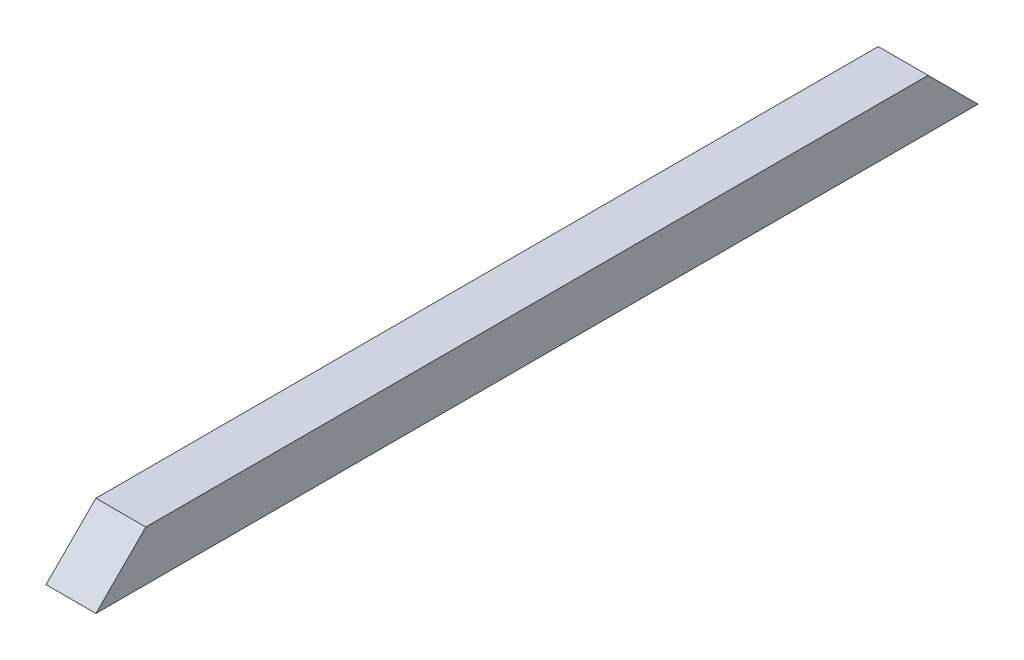
SolidWorks part; units mm, degrees
material "Plain Carbon Steel"
ref_plane "Front Plane" through (0, 0, 0) normal (0, 0, 1) x (1, 0, 0)
ref_plane "Top Plane" through (0, 0, 0) normal (0, 1, 0) x (1, 0, 0)
ref_plane "Right Plane" through (0, 0, 0) normal (1, 0, 0) x (0, 0, -1)
sketch "Sketch1" plane through (0, 0, 0) normal (0, 0, 1) x (1, 0, 0)
  line L1 (0, 0) -> (20, 0)
  line L2 (0, 0) -> (0, -20)
  line L3 (0, -20) -> (20, -20)
  line L4 (20, 0) -> (20, -20)
  dimension "D1" = 20
extrude "Boss-Extrude1" add sketch "Sketch1" along normal blind 600
sketch "Sketch2" plane through (20, 0, 0) normal (1, 0, 0) x (0, 0, -1)
  line L0 (-600, -20) -> (-600, 0)
  line L1 (-600, 0) -> (-580, 0)
  line L2 (-600, 0) -> (0, 0) construction
  line L3 (-580, 0) -> (-600, -20)
  line L4 (-266.4373, 0) -> (-246.4466, -20)
  line L5 (-578.7868, 312.3402) -> (517.2287, -783.6753) construction
  line L6 (-600, -20) -> (0, -20) construction
  line L7 (-246.4466, -20) -> (0, -20)
  line L8 (0, -20) -> (0, 0)
  line L9 (0, 0) -> (-266.4373, 0)
extrude "Cut-Extrude1" cut sketch "Sketch2" against normal through all both and the other way through all
